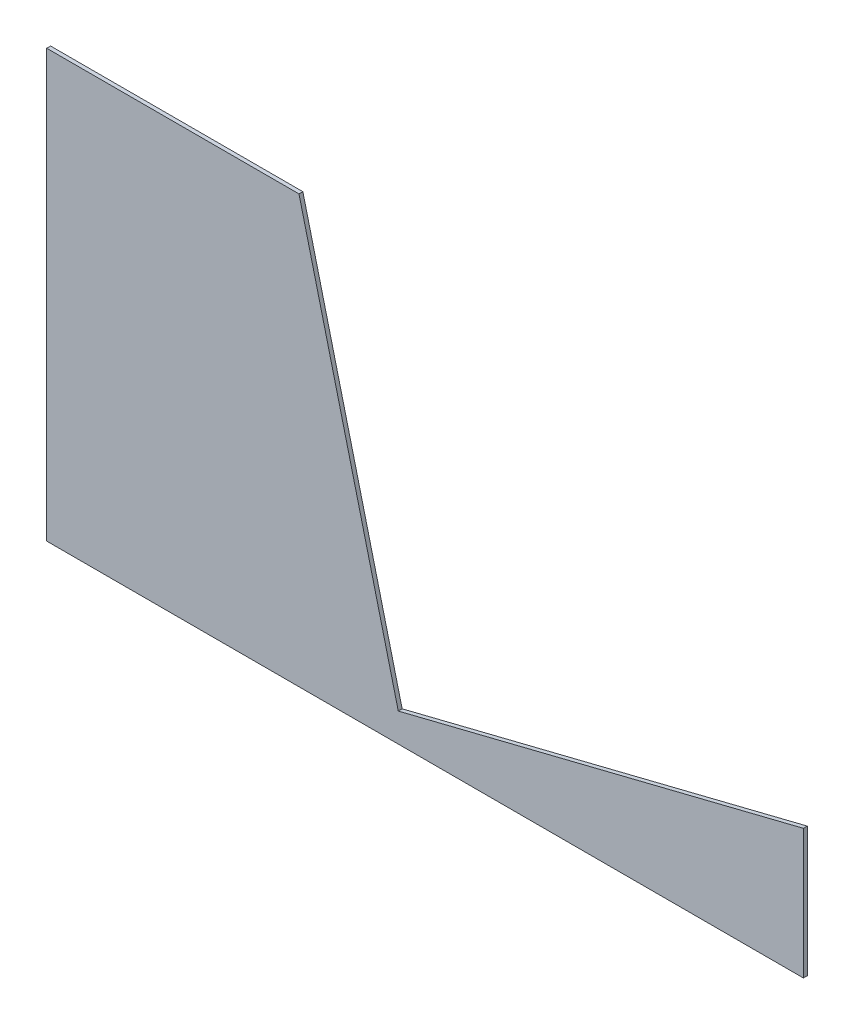
SolidWorks part; units mm, degrees
ref_plane "Front Plane" through (0, 0, 0) normal (0, 0, 1) x (1, 0, 0)
ref_plane "Top Plane" through (0, 0, 0) normal (0, 1, 0) x (1, 0, 0)
ref_plane "Right Plane" through (0, 0, 0) normal (1, 0, 0) x (0, 0, -1)
sketch "Sketch1" plane through (0, 0, 0) normal (0, 0, 1) x (1, 0, 0)
  line L0 (345, -262) -> (646.1882, -1470) construction
  line L1 (646.1882, -1470) -> (345, -1470)
  line L2 (345, -1470) -> (345, -262) construction
  line L3 (168.0188, -151.5343) -> (240.5954, -442.623) construction
  line L4 (240.5954, -442.623) -> (521.9812, -372.4657) construction
  line L5 (521.9812, -372.4657) -> (449.4046, -81.377) construction
  line L6 (449.4046, -81.377) -> (168.0188, -151.5343) construction
  line L7 (308.7117, -116.4556) -> (381.2883, -407.5444) construction
  line L8 (0, 0) -> (0, -679.7638) construction
  line L9 (0, 0) -> (710.7258, 0) construction
  line L10 (0, -450) -> (1182.4212, -450) construction
  line L11 (150, 0) -> (150, -450) construction
  line L12 (150, -340) -> (215.0086, -340)
  line L13 (215.0086, -340) -> (240.5954, -442.623)
  line L14 (345, -450) -> (150, -450)
  line L15 (150, -340) -> (150, -450)
  line L16 (240.5954, -442.623) -> (345, -416.592)
  line L17 (345, -416.592) -> (345, -450)
  line L18 (345, -262) -> (752.2849, -1895.5305) construction
  line L19 (-431.775, -800) -> (1703.6811, -800) construction
  line L20 (479.1385, -800) -> (530.8538, -777.2641)
  point P2 (345, -262)
  dimension "D1" = 90
  dimension "D2" = 345
  dimension "D3" = 262
  dimension "D4" = 1470
  dimension "D5" = 290
  dimension "D6" = 14
  dimension "D7" = 300
  dimension "D8" = 450
  dimension "D9" = 150
  dimension "D10" = 110
  dimension "D12" = 479.1385
extrude "Boss-Extrude1" add sketch "Sketch1" along normal blind 1 contours L12 L15 L14 L13
